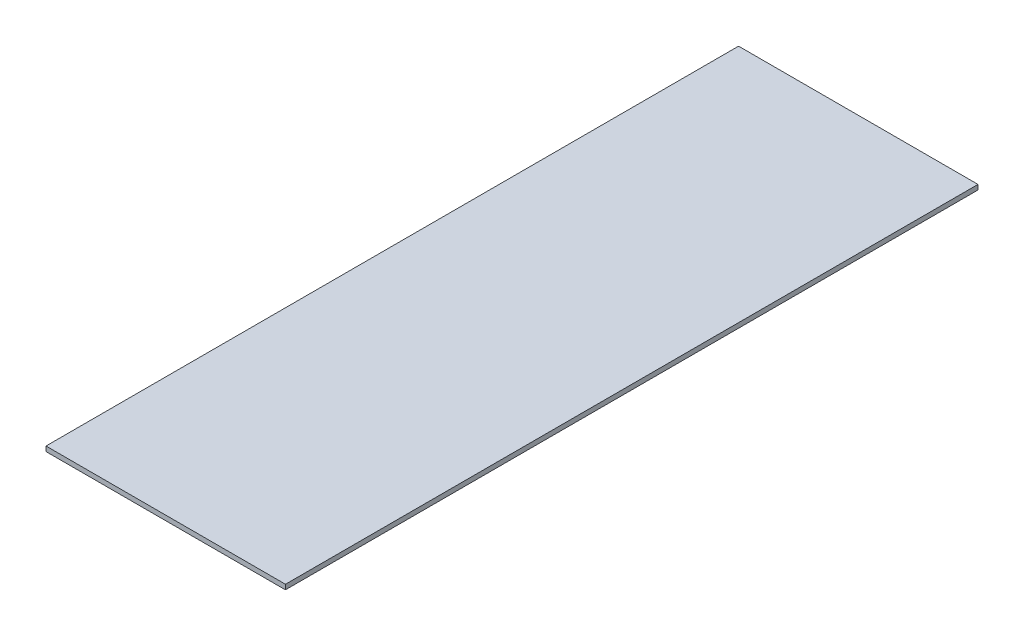
SolidWorks part; units mm, degrees
ref_plane "Front Plane" through (0, 0, 0) normal (0, 0, 1) x (1, 0, 0)
ref_plane "Top Plane" through (0, 0, 0) normal (0, 1, 0) x (1, 0, 0)
ref_plane "Right Plane" through (0, 0, 0) normal (1, 0, 0) x (0, 0, -1)
sketch "Sketch1" plane through (0, 0, 0) normal (0, 0, 1) x (1, 0, 0)
  line L1 (-78.3443, 70.1122) -> (78.3443, 70.1122)
  line L2 (-78.3443, 70.1122) -> (-78.3443, 73.2872)
  line L3 (-78.3443, 73.2872) -> (78.3443, 73.2872)
  line L4 (78.3443, 70.1122) -> (78.3443, 73.2872)
  point P0 (-88.3432, 73.1449)
  point P8 (0, 70.1122)
  dimension "D1" = 3.175
  dimension "D2" = 10
extrude "Boss-Extrude1" add sketch "Sketch1" against normal blind 453.2
